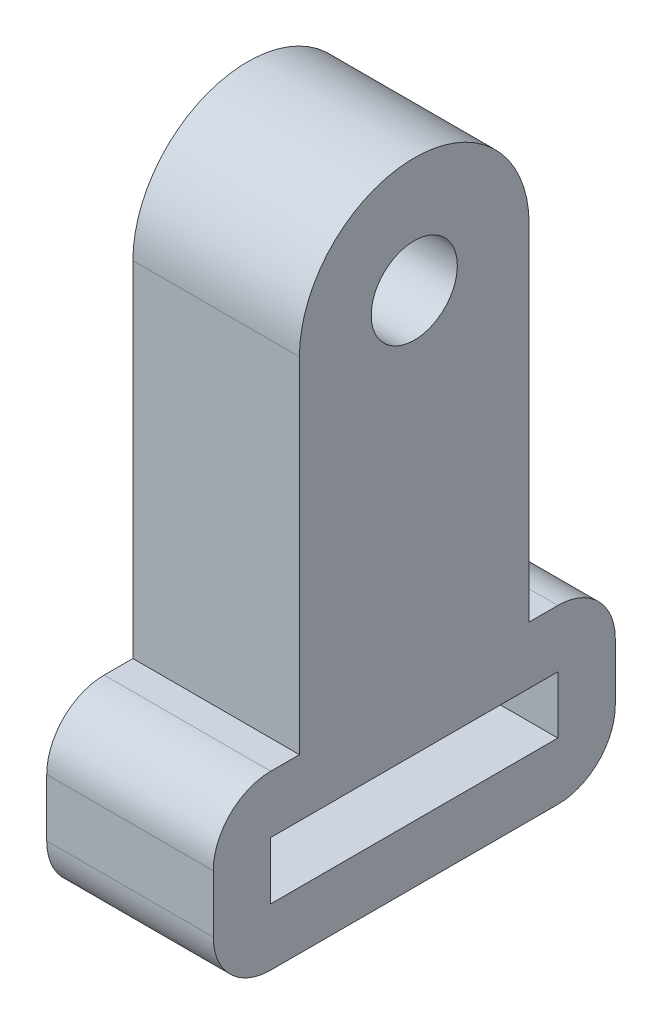
SolidWorks part; units mm, degrees
ref_plane "Alzado" through (0, 0, 0) normal (0, 0, 1) x (1, 0, 0)
ref_plane "Planta" through (0, 0, 0) normal (0, 1, 0) x (1, 0, 0)
ref_plane "Vista lateral" through (0, 0, 0) normal (1, 0, 0) x (0, 0, -1)
sketch "Croquis1" plane through (0, 0, 0) normal (1, 0, 0) x (0, 0, -1)
  line L2 (-7, 1) -> (-7, -1)
  line L3 (-5, -3) -> (5, -3)
  line L4 (7, 1) -> (7, -1)
  line L5 (-7, 3) -> (7, -3) construction
  line L6 (-7, -3) -> (7, 3) construction
  line L7 (-5, 1) -> (5, 1)
  line L8 (-5, 1) -> (-5, -1)
  line L9 (-5, -1) -> (5, -1)
  line L10 (5, 1) -> (5, -1)
  line L11 (-5, 1) -> (5, -1) construction
  line L12 (-5, -1) -> (5, 1) construction
  line L15 (-7, 3) -> (7, 3) construction
  line L27 (-4, 3) -> (-5, 3)
  line L28 (4, 3) -> (5, 3)
  line L35 (0, 3) -> (0, 15) construction
  line L36 (-4, 15) -> (-4, 3)
  line L39 (4, 15) -> (4, 3)
  circle A1 centre (0, 15) radius 1.5
  arc A2 (4, 15) -> (-4, 15) centre (0, 15) ccw
  arc A3 (5, -3) -> (7, -1) centre (5, -1) ccw
  arc A4 (5, 3) -> (7, 1) centre (5, 1) cw
  arc A5 (-7, -1) -> (-5, -3) centre (-5, -1) ccw
  arc A6 (-5, 3) -> (-7, 1) centre (-5, 1) ccw
  point P0 (0, 0)
  point P6 (0, 0)
  dimension "D18" = 8
  dimension "D17" = 3
  dimension "D6" = 2
  dimension "D2" = 14
  dimension "D3" = 2
  dimension "D4" = 10
  dimension "D5" = 6
  dimension "D16" = 12
  dimension "D23" = 2
extrude "Saliente-Extruir1" add sketch "Croquis1" along normal mid plane 5.8
